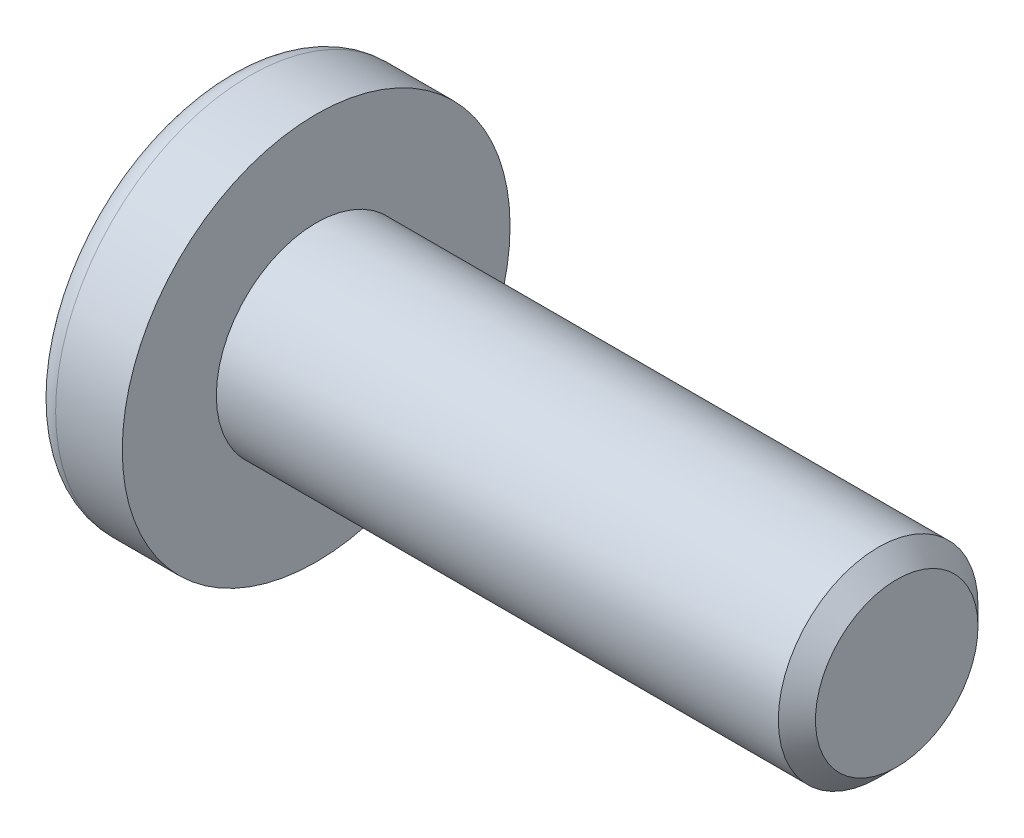
SolidWorks part; units mm, degrees
material "Alloy Steel"
ref_plane "Plane1" through (0, 0, 0) normal (0, 0, 1) x (1, 0, 0)
ref_plane "Plane2" through (0, 0, 0) normal (0, 1, 0) x (1, 0, 0)
ref_plane "Plane3" through (0, 0, 0) normal (1, 0, 0) x (0, 0, -1)
sketch "BodySke" plane through (0, 0, 0) normal (0, 0, 1) x (1, 0, 0)
  line L0 (1.5748, 1.0922) -> (1.5748, 2.1209)
  line L1 (1.8021, 6.35) -> (1.8021, -3.175) construction
  line L2 (-25.4, 0) -> (127, 0) construction
  line L3 (7.9248, 0) -> (0, 0)
  line L4 (1.5748, 1.0922) -> (7.9248, 1.0922)
  line L5 (7.9248, 1.0922) -> (7.9248, 0)
  line L6 (0.8457, 2.1209) -> (1.5748, 2.1209)
  line L7 (1.5748, -1.0922) -> (7.9248, -1.0922) construction
  line L8 (1.5748, 6.35) -> (1.5748, -3.175) construction
  arc A0 (0.6381, 2.0132) -> (0, 0) centre (3.495, 0) ccw
  arc A2 (0.6381, 2.0132) -> (0.8457, 2.1209) centre (0.8457, 1.8669) cw
  dimension "Head_crown_rad" = 3.495
  dimension "Head_fillet_rad" = 0.254
  dimension "Diameter" = 2.1844
  dimension "Length" = 6.35
  dimension "Head_ht" = 1.5748
  dimension "Head_dia" = 4.2418
  dimension "Advance" = 0.4547
  dimension "Thread_nom" = 6.35
revolve "Base-Revolve" add sketch "BodySke" angle 360 about L2
cosmetic thread "ThreadCosmetic" parameters "Thread_length"=5.8953, "Thread_minor"=1.6459
sketch "Sketch3" plane through (0, 0, 0) normal (1, 0, 0) x (0, 0, -1)
  line L0 (0.3429, -1.3843) -> (-0.3429, -1.3843)
  line L1 (0.3429, -1.3843) -> (0.3429, 1.3843)
  line L2 (-0.3429, 1.3843) -> (0.3429, 1.3843)
  line L3 (-0.3429, 1.3843) -> (-0.3429, -1.3843)
  dimension "Cross_dia" = 2.7686
  dimension "D1" = 1.3843
  dimension "Cross_width" = 0.6858
  dimension "D2" = 0.3429
ref_plane "Plane4" through (1.4986, 0, 0) normal (1, 0, 0) x (0, 0, -1)
sketch "Sketch4" plane through (1.4986, 0, 0) normal (1, 0, 0) x (0, 0, -1)
  line L0 (0.1714, -0.1715) -> (-0.1714, -0.1715)
  line L1 (0.1714, -0.1715) -> (0.1714, 0.1714)
  line L2 (-0.1714, 0.1714) -> (0.1714, 0.1714)
  line L3 (-0.1714, 0.1714) -> (-0.1714, -0.1715)
  dimension "D2" = 0.3429
  dimension "D1" = 0.3429
  dimension "D3" = 0.1714
  dimension "D4" = 0.1714
loft "Cut-Loft1" cut profiles "Sketch3", "Sketch4"
pattern_circular "CirPattern1" count 2 every 90 about axis through (0, 0, 0) along (1, 0, 0) of "Cut-Loft1"
chamfer "Chamfer1" distance 0.2032 angle 45 1 edges at (7.9248, 0, 1.0922)
equation "\"D1@Sketch3\" = \"Cross_dia@Sketch3\" / 2"
equation "\"D2@Sketch3\" = \"Cross_width@Sketch3\" / 2"
equation "\"D1@Sketch4\" = \"Cross_width@Sketch3\" *.5"
equation "\"D2@Sketch4\" = \"D1@Sketch4\""
equation "\"D3@Sketch4\" = \"D1@Sketch4\" / 2"
equation "\"D4@Sketch4\" = \"D2@Sketch4\" / 2"
equation "\"Thread_length@ThreadCosmetic\" = ((sgn( (\"Length@BodySke\" - \"Advance@BodySke\" ) - \"Thread_nom@BodySke\" )-1)*( (\"Length@BodySke\" - \"Advance@BodySke\" ) - \"Thread_nom@BodySke\" ))/-2+ \"Thread_nom@BodySke\""
